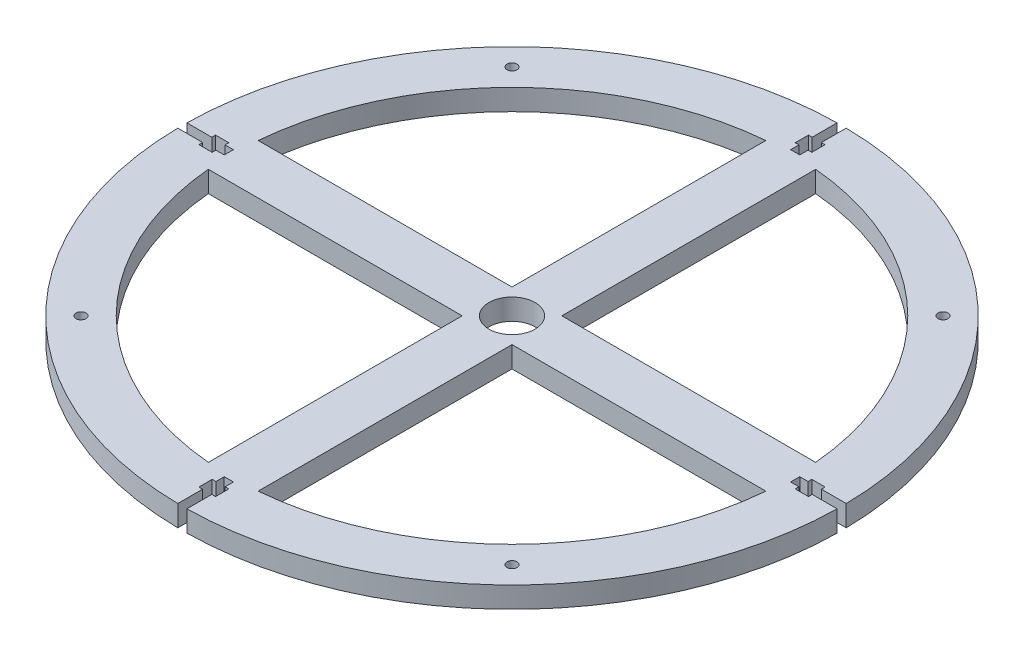
SolidWorks part; units mm, degrees
material "6061 Alloy"
ref_plane "Front Plane" through (0, 0, 0) normal (0, 0, 1) x (1, 0, 0)
ref_plane "Top Plane" through (0, 0, 0) normal (0, 1, 0) x (1, 0, 0)
ref_plane "Right Plane" through (0, 0, 0) normal (1, 0, 0) x (0, 0, -1)
sketch "Sketch1" plane through (0, 0, 0) normal (0, 1, 0) x (1, 0, 0)
  line L0 (0, -99.238) -> (0, 99.238) construction
  line L1 (-99.238, 0) -> (99.238, 0) construction
  line L2 (-98.9542, -7.5) -> (98.9542, -7.5)
  line L3 (7.5, -98.9542) -> (7.5, 98.9542)
  line L4 (-98.9542, 7.5) -> (98.9542, 7.5)
  line L5 (-7.5, -98.9542) -> (-7.5, 98.9542)
  line L6 (-7.5, -99.238) -> (-7.5, 99.238) construction
  line L7 (7.5, -99.238) -> (7.5, 99.238) construction
  line L8 (-99.238, -7.5) -> (99.238, -7.5) construction
  line L9 (-99.238, 7.5) -> (99.238, 7.5) construction
  circle A0 centre (0, 0) radius 100 construction
  circle A1 centre (0, 0) radius 99.238
  circle A2 centre (0, 0) radius 84.238
  point P7 (0, 0)
  point P11 (0, 0)
  dimension "D1" = 200
  dimension "D2" = 0.762
  dimension "D3" = 15
  dimension "D4" = 7.5
  dimension "D5" = 7.5
extrude "Boss-Extrude1" add sketch "Sketch1" along normal mid plane 6.35 contours A2 L2 A1 L5 | A2 L4 A1 L2 | A2 L5 A1 L4 | A2 L3 A1 L5 | A2 L4 A1 L3 | A2 L2 A1 L4 | A2 L3 A1 L2 | A2 L5 A1 L3 | L5 A2 L3 L2 | L4 A2 L2 L5 | L3 A2 L5 L4 | L2 A2 L4 L3 | L5 L2 L3 L4
sketch "Sketch2" plane through (0, 0, 0) normal (0, 1, 0) x (1, 0, 0)
  line L0 (-1.375, 85.238) -> (-1.375, 99.238)
  line L1 (-1.375, 85.238) -> (1.375, 85.238)
  line L2 (-1.375, 99.238) -> (1.375, 99.238)
  line L3 (1.375, 85.238) -> (1.375, 99.238)
  line L4 (-1.375, 85.238) -> (1.375, 99.238) construction
  line L5 (-1.375, 99.238) -> (1.375, 85.238) construction
  line L6 (-2.5, 87.738) -> (-2.5, 91.738)
  line L7 (-2.5, 87.738) -> (2.5, 87.738)
  line L8 (-2.5, 91.738) -> (2.5, 91.738)
  line L9 (2.5, 87.738) -> (2.5, 91.738)
  line L10 (-2.5, 87.738) -> (2.5, 91.738) construction
  line L11 (-2.5, 91.738) -> (2.5, 87.738) construction
  line L12 (0, -1000) -> (0, 49000) construction
  line L13 (-1000, 0) -> (49000, 0) construction
  circle A0 centre (0, 0) radius 99.238 construction
  point P1 (0, 92.238)
  point P2 (0, 89.738)
  dimension "D1" = 2.75
  dimension "D2" = 14
  dimension "D3" = 4
  dimension "D4" = 5
  dimension "D5" = 2.5
extrude "Cut-Extrude1" cut sketch "Sketch2" against normal through all both and the other way through all contours L7 L0 L1 L3 | L8 L0 L7 L3 | L7 L9 L8 L3 | L0 L8 L3 L2 | L8 L6 L7 L0
pattern_circular "CirPattern1" count 4 over 360 about axis through (0, 0, 0) along (0, 1, 0) of "Cut-Extrude1"
hole_wizard "Ø3.0 (3) Diameter Hole1" positions "Sketch3" profile "Sketch4" hole size "Ø3.0" standard "ANSI Metric" end condition up to next
sketch "Sketch3" plane through (0, 3.175, 0) normal (0, 1, 0) x (1, 0, 0)
  line L0 (-70.1719, -70.1719) -> (70.1719, 70.1719) construction
  line L2 (-70.1719, 70.1719) -> (70.1719, -70.1719) construction
  line L4 (70.1719, 70.1719) -> (59.5653, 59.5653)
  line L6 (70.1719, -70.1719) -> (59.5653, -59.5653)
  line L8 (-70.1719, -70.1719) -> (-59.5653, -59.5653)
  line L10 (-70.1719, 70.1719) -> (-59.5653, 59.5653)
  arc A0 (99.2285, 1.375) -> (1.375, 99.2285) centre (0, 0) ccw construction
  arc A1 (1.375, -99.2285) -> (99.2285, -1.375) centre (0, 0) ccw construction
  arc A2 (83.9035, 7.5) -> (7.5, 83.9035) centre (0, 0) ccw construction
  arc A3 (7.5, -83.9035) -> (83.9035, -7.5) centre (0, 0) ccw construction
  arc A4 (-83.9035, -7.5) -> (-7.5, -83.9035) centre (0, 0) ccw construction
  arc A5 (-7.5, 83.9035) -> (-83.9035, 7.5) centre (0, 0) ccw construction
  point P107 (0, 0)
  point P324 (0, 0)
  point P360 (-64.8686, 64.8686)
  point P362 (64.8686, 64.8686)
  point P364 (64.8686, -64.8686)
  point P366 (-64.8686, -64.8686)
sketch "Sketch4" plane through (-64.8686, 3.175, 64.8686) normal (1, 0, 0) x (0, 0, 1)
  line L0 (0, 0) -> (0, 6.35)
  line L1 (0, 6.35) -> (1.5, 6.35)
  line L2 (1.5, 6.35) -> (1.5, 0)
  line L5 (1.5, 0) -> (0, 0)
  line L11 (0, -6.35) -> (0, 107.95) construction
  dimension "Thru Hole Dia." = 3
  dimension "Thru Hole Depth" = 6.35
hole_wizard "1/2 Clearance Hole1" positions "Sketch5" profile "Sketch6" hole size "1/2" standard "ANSI Inch" end condition up to next
sketch "Sketch5" plane through (0, 3.175, 0) normal (0, 1, 0) x (1, 0, 0)
  point P0 (0, 0)
sketch "Sketch6" plane through (0, 3.175, 0) normal (1, 0, 0) x (0, 0, 1)
  line L0 (0, 0) -> (0, 6.35)
  line L1 (0, 6.35) -> (6.9456, 6.35)
  line L2 (6.9456, 6.35) -> (6.9456, 0)
  line L5 (6.9456, 0) -> (0, 0)
  line L11 (0, -6.35) -> (0, 107.95) construction
  dimension "Thru Hole Dia." = 13.8913
  dimension "Thru Hole Depth" = 6.35
